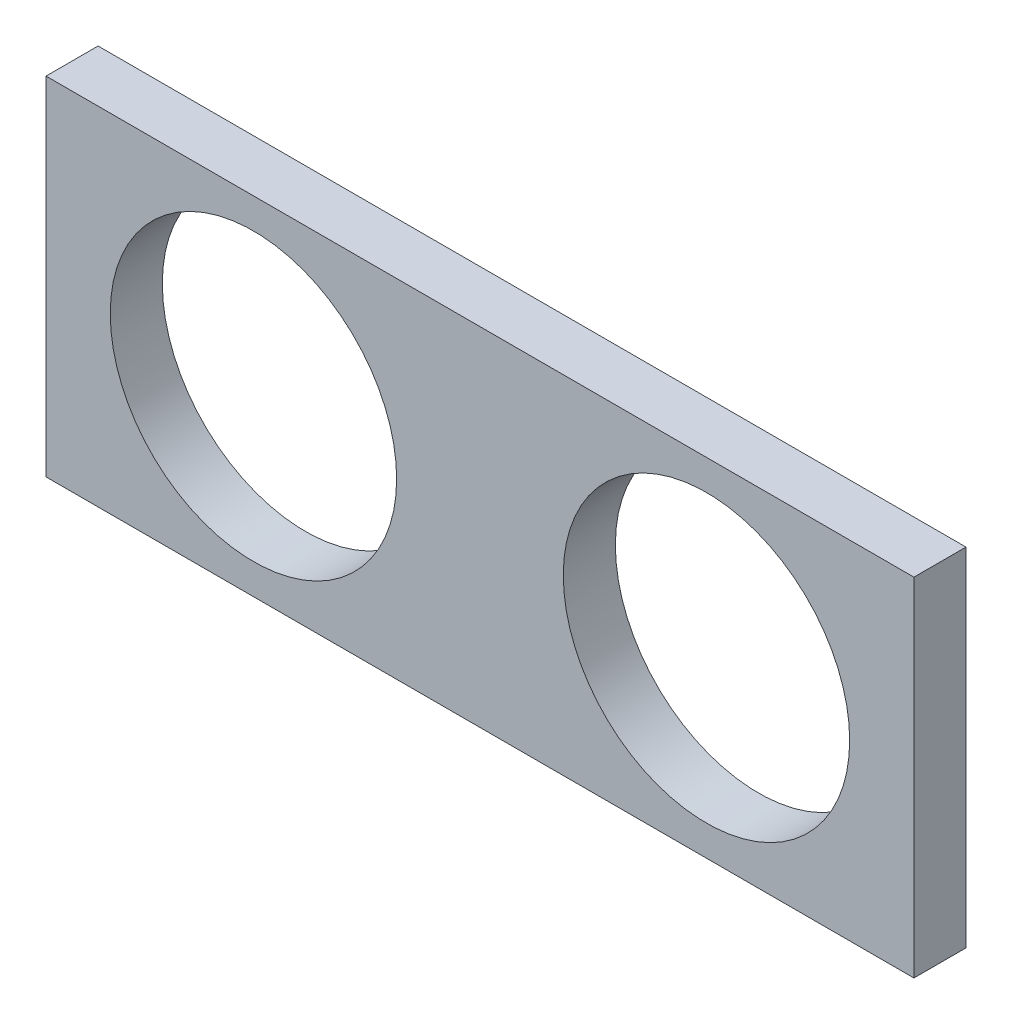
SolidWorks part; units mm, degrees
ref_plane "前视基准面" through (0, 0, 0) normal (0, 0, 1) x (1, 0, 0)
ref_plane "上视基准面" through (0, 0, 0) normal (0, 1, 0) x (1, 0, 0)
ref_plane "右视基准面" through (0, 0, 0) normal (1, 0, 0) x (0, 0, -1)
other "Configuration Table"
sketch "草图1" plane through (0, 0, 0) normal (0, 0, 1) x (1, 0, 0)
  line L1 (-25, -10) -> (25, -10)
  line L2 (-25, -10) -> (-25, 10)
  line L3 (-25, 10) -> (25, 10)
  line L4 (25, -10) -> (25, 10)
  line L5 (-25, -10) -> (25, 10) construction
  line L6 (-25, 10) -> (25, -10) construction
  circle A0 centre (-13.05, 0) radius 8.25
  circle A1 centre (13.05, 0) radius 8.25
  point P0 (0, 0)
  dimension "D3" = 16.5
  dimension "D4" = 16.5
  dimension "D1" = 50
  dimension "D2" = 20
extrude "凸台-拉伸1" add sketch "草图1" along normal blind 3
